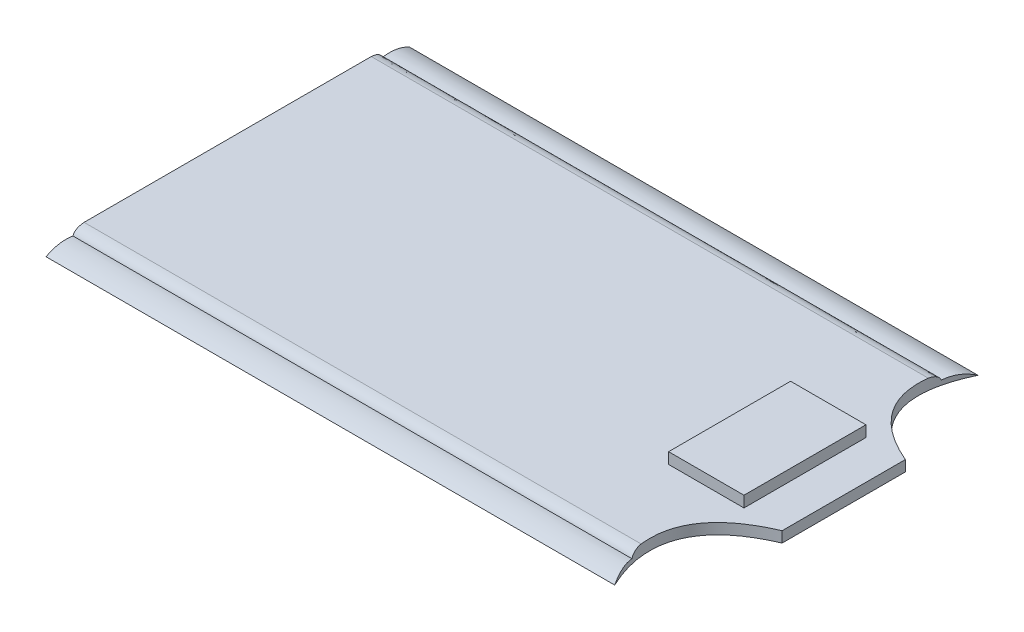
SolidWorks part; units mm, degrees
ref_plane "Front Plane" through (0, 0, 0) normal (0, 0, 1) x (1, 0, 0)
ref_plane "Top Plane" through (0, 0, 0) normal (0, 1, 0) x (1, 0, 0)
ref_plane "Right Plane" through (0, 0, 0) normal (1, 0, 0) x (0, 0, -1)
sketch "Sketch1" plane through (0, 0, 0) normal (1, 0, 0) x (0, 0, -1)
  line L1 (575, -17) -> (-575, -17)
  line L2 (575, -17) -> (575, 17)
  line L3 (575, 17) -> (-575, 17)
  line L4 (-575, -17) -> (-575, 17)
  line L5 (575, -17) -> (-575, 17) construction
  line L6 (575, 17) -> (-575, -17) construction
  point P0 (0, 0)
  dimension "D1" = 1150
  dimension "D2" = 34
extrude "Boss-Extrude1" add sketch "Sketch1" along normal blind 1950
sketch "Sketch2" plane through (1950, 0, 0) normal (1, 0, 0) x (0, 0, -1)
  line L0 (454.5069, 17) -> (575, 17)
  line L1 (575, 17) -> (-575, 17) construction
  line L2 (-454.5069, 17) -> (-575, 17)
  line L3 (-575, 17) -> (-575, -17)
  line L4 (575, 17) -> (575, -17)
  spline S0 degree 2 poles (-454.5069, 17) (-483.1492, 14.5776) (-489.6826, -2.777) knots 0 0 0 0.737775 0.737775 0.737775
  spline S1 degree 2 poles (-489.6826, -2.777) (-534.7764, 4.5224) (-575, -17) knots 0 0 0 1 1 1
  spline S2 degree 2 poles (489.6826, -2.777) (534.7764, 4.5224) (575, -17) knots 0 0 0 1 1 1
  spline S3 degree 2 poles (454.5069, 17) (483.1492, 14.5776) (489.6826, -2.777) knots 0 0 0 0.737775 0.737775 0.737775
extrude "Cut-Extrude3" cut sketch "Sketch2" against normal blind 1950
sketch "Sketch3" plane through (0, -17, 0) normal (0, -1, 0) x (1, 0, 0)
  line L0 (1950, 575) -> (1950, -575) construction
  line L1 (1950, 575) -> (0, 575) construction
  line L2 (1800, 575) -> (1950, 575)
  line L3 (1950, 575) -> (1950, 195)
  line L4 (1950, -195) -> (1950, -575)
  line L5 (1950, -575) -> (1800, -575)
  spline S0 degree 2 poles (1950, 195) (1676.1626, 312.4178) (1800, 575) knots 0 0 0 1 1 1
  spline S1 degree 2 poles (1950, -195) (1676.1626, -312.4178) (1800, -575) knots 0 0 0 1 1 1
  dimension "D2" = 150
extrude "Cut-Extrude4" cut sketch "Sketch3" against normal blind 1950
sketch "Sketch4" plane through (0, 17, 0) normal (0, 1, 0) x (1, 0, 0)
  line L1 (1827.3061, 193.0638) -> (1588.7232, 193.0638)
  line L2 (1827.3061, 193.0638) -> (1827.3061, -193.0638)
  line L3 (1827.3061, -193.0638) -> (1588.7232, -193.0638)
  line L4 (1588.7232, 193.0638) -> (1588.7232, -193.0638)
  line L5 (1827.3061, 193.0638) -> (1588.7232, -193.0638) construction
  line L6 (1827.3061, -193.0638) -> (1588.7232, 193.0638) construction
  point P0 (1708.0147, 0)
extrude "Boss-Extrude5" add sketch "Sketch4" along normal blind 35
